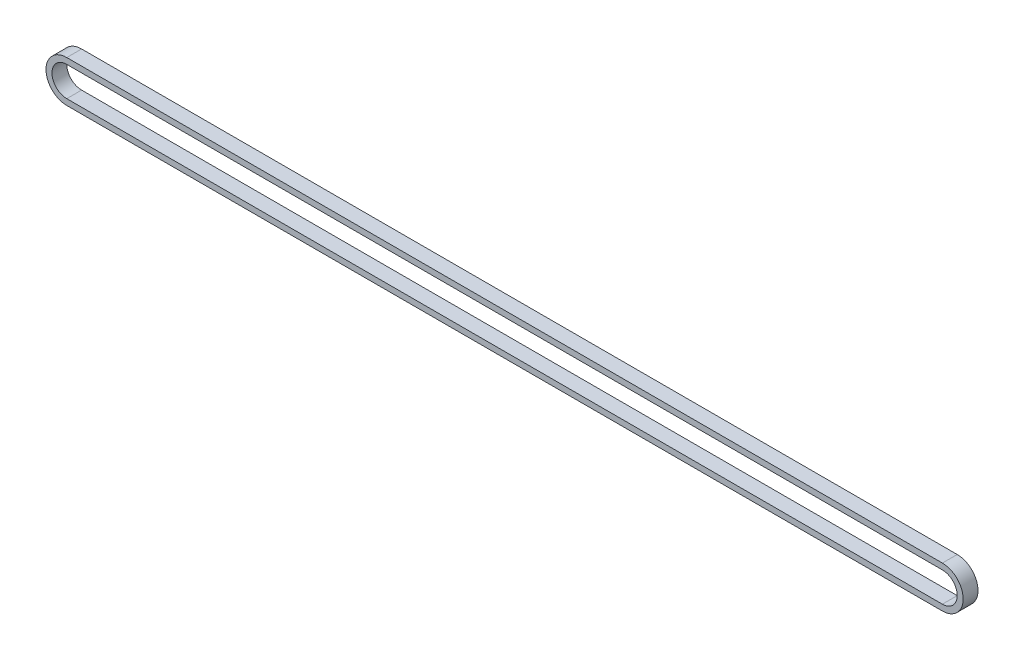
SolidWorks part; units mm, degrees
ref_plane "Front Plane" through (0, 0, 0) normal (0, 0, 1) x (1, 0, 0)
ref_plane "Top Plane" through (0, 0, 0) normal (0, 1, 0) x (1, 0, 0)
ref_plane "Right Plane" through (0, 0, 0) normal (1, 0, 0) x (0, 0, -1)
sketch "Sketch1" plane through (0, 0, 0) normal (0, 0, 1) x (1, 0, 0)
  line L0 (-281.7463, 154.1199) -> (308.2537, 154.1199)
  line L1 (-281.7463, 134.1199) -> (308.2537, 134.1199)
  line L2 (-281.7463, 158.1199) -> (308.2537, 158.1199)
  line L3 (-281.7463, 130.1199) -> (308.2537, 130.1199)
  arc A0 (-281.7463, 154.1199) -> (-281.7463, 134.1199) centre (-281.7463, 144.1199) ccw
  arc A1 (308.2537, 154.1199) -> (308.2537, 134.1199) centre (308.2537, 144.1199) cw
  arc A2 (308.2537, 158.1199) -> (308.2537, 130.1199) centre (308.2537, 144.1199) cw
  arc A3 (-281.7463, 158.1199) -> (-281.7463, 130.1199) centre (-281.7463, 144.1199) ccw
  dimension "D1" = 590
  dimension "D2" = 10
  dimension "D3" = 4
extrude "Boss-Extrude1" add sketch "Sketch1" along normal blind 10
